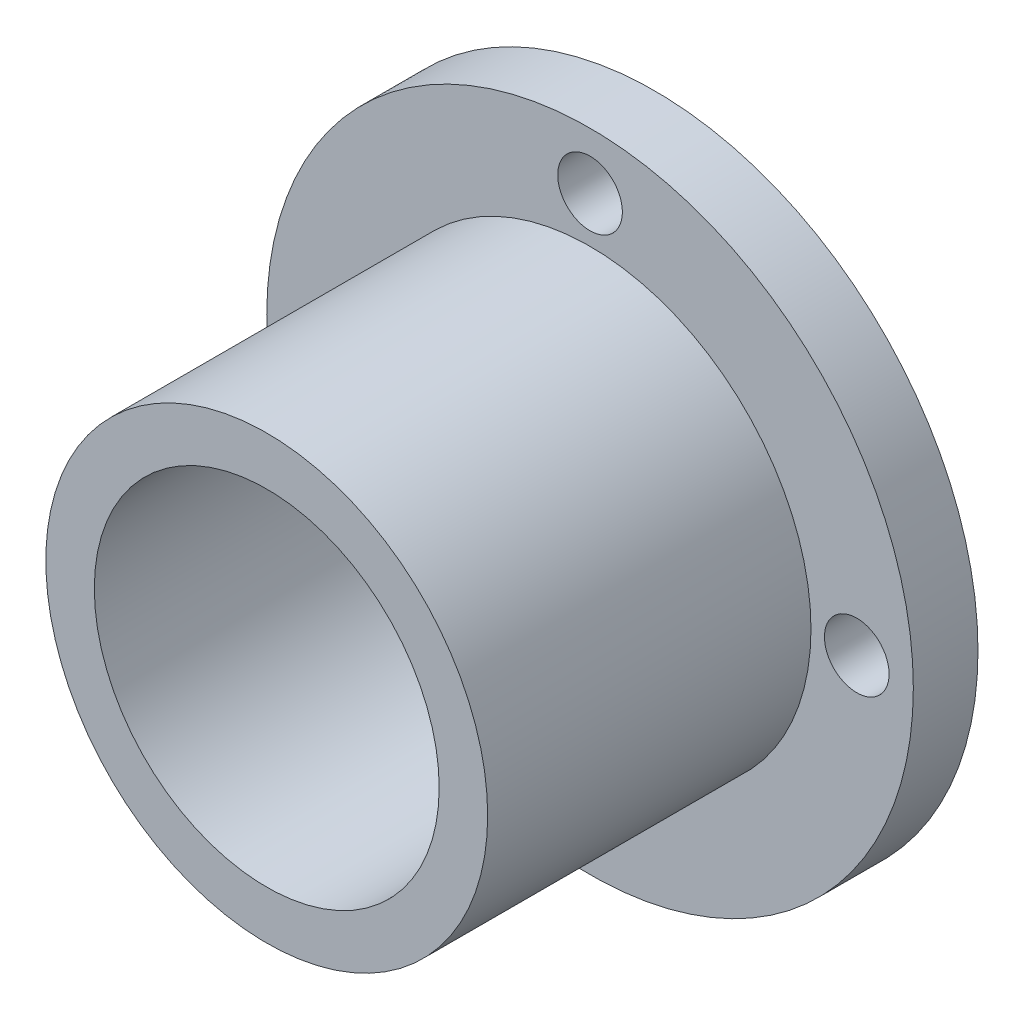
SolidWorks part; units mm, degrees
material "6061 Alloy"
ref_plane "Front Plane" through (0, 0, 0) normal (0, 0, 1) x (1, 0, 0)
ref_plane "Top Plane" through (0, 0, 0) normal (0, 1, 0) x (1, 0, 0)
ref_plane "Right Plane" through (0, 0, 0) normal (1, 0, 0) x (0, 0, -1)
sketch "Sketch1" plane through (0, 0, 0) normal (0, 0, 1) x (1, 0, 0)
  circle A0 centre (0, 0) radius 13.668
  circle A1 centre (0, 0) radius 10.668
  dimension "D1" = 21.336
  dimension "D2" = 3
extrude "Boss-Extrude1" add sketch "Sketch1" along normal blind 20
sketch "Sketch2" plane through (0, 0, 0) normal (0, 0, -1) x (-1, 0, 0)
  circle A0 centre (0, 0) radius 20
  dimension "D1" = 40
extrude "Boss-Extrude2" add sketch "Sketch2" along normal blind 4
sketch "Sketch3" plane through (0, 0, 0) normal (0, 0, 1) x (1, 0, 0)
  circle A0 centre (0, 0) radius 16.5 construction
  circle A1 centre (0, 16.5) radius 2
  circle A2 centre (16.5, 0) radius 2
  circle A3 centre (0, -16.5) radius 2
  circle A4 centre (-16.5, 0) radius 2
  point P13 (0, 0)
  dimension "D1" = 33
  dimension "D2" = 4
  dimension "D3" = 4
extrude "M4_DRILL" cut sketch "Sketch3" against normal blind 4
